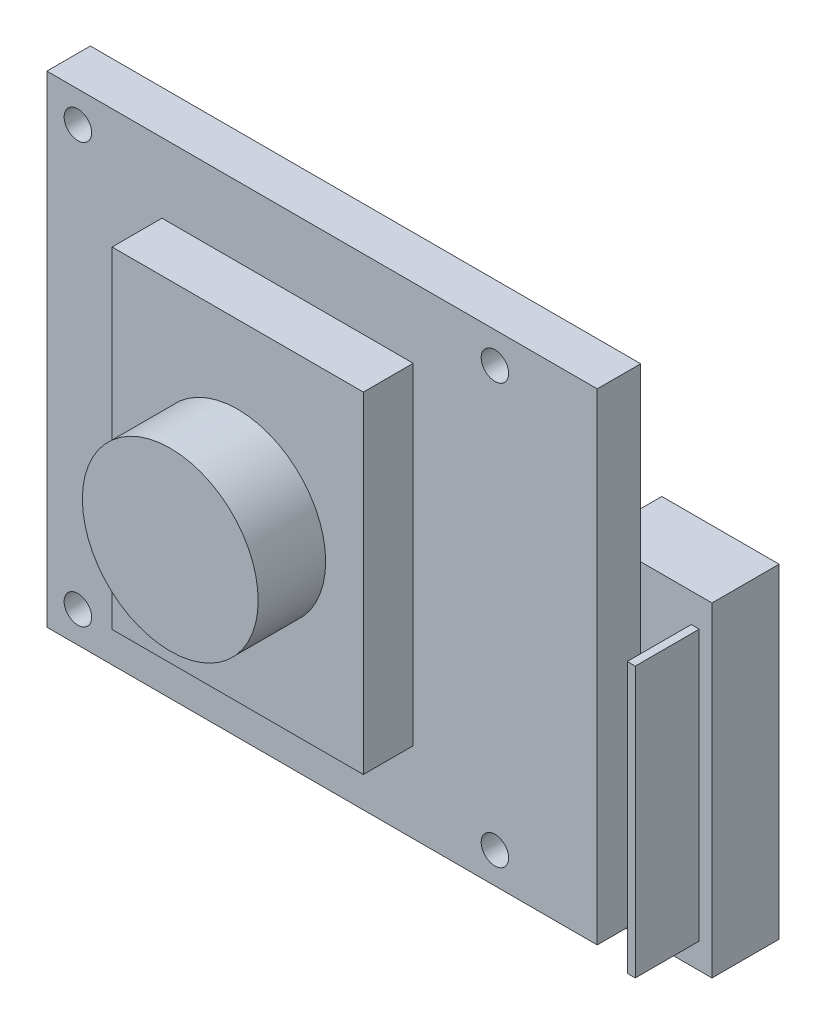
SolidWorks part; units mm, degrees
ref_plane "Front Plane" through (0, 0, 0) normal (0, 0, 1) x (1, 0, 0)
ref_plane "Top Plane" through (0, 0, 0) normal (0, 1, 0) x (1, 0, 0)
ref_plane "Right Plane" through (0, 0, 0) normal (1, 0, 0) x (0, 0, -1)
sketch "Sketch1" plane through (0, 0, 0) normal (0, 0, 1) x (1, 0, 0)
  line L1 (-43.7261, 0) -> (0, 0)
  line L2 (-43.7261, 0) -> (-43.7261, 38.2651)
  line L3 (-43.7261, 38.2651) -> (0, 38.2651)
  line L4 (0, 0) -> (0, 38.2651)
  dimension "D1" = 38.2651
  dimension "D2" = 43.7261
extrude "Boss-Extrude1" add sketch "Sketch1" along normal blind 3.4544
sketch "Sketch2" plane through (0, 0, 0) normal (0, 0, -1) x (-1, 0, 0)
  line L0 (0, 0) -> (0, 38.2651) construction
  line L1 (3.6576, -1.1684) -> (-5.6642, -1.1684)
  line L2 (3.6576, -1.1684) -> (3.6576, 24.638)
  line L3 (3.6576, 24.638) -> (-5.6642, 24.638)
  line L4 (-5.6642, -1.1684) -> (-5.6642, 24.638)
  line L5 (43.7261, 0) -> (0, 0) construction
  dimension "D1" = 9.3218
  dimension "D2" = 25.8064
  dimension "D3" = 5.6642
  dimension "D4" = 1.1684
extrude "Boss-Extrude2" add sketch "Sketch2" along normal blind 5.334
sketch "Sketch3" plane through (0, 0, 0) normal (0, 0, 1) x (1, 0, 0)
  line L0 (5.6642, 24.638) -> (5.6642, -1.1684) construction
  line L1 (4.0132, 0.8636) -> (4.6482, 0.8636)
  line L2 (4.0132, 0.8636) -> (4.0132, 22.3266)
  line L3 (4.0132, 22.3266) -> (4.6482, 22.3266)
  line L4 (4.6482, 0.8636) -> (4.6482, 22.3266)
  line L5 (5.6642, -1.1684) -> (-3.6576, -1.1684) construction
  dimension "D1" = 21.463
  dimension "D2" = 0.635
  dimension "D3" = 1.016
  dimension "D4" = 2.032
extrude "Boss-Extrude3" add sketch "Sketch3" along normal blind 5.08
sketch "Sketch4" plane through (0, 0, 0) normal (0, 0, -1) x (-1, 0, 0)
  line L2 (0, 38.2651) -> (43.7261, 38.2651) construction
  line L3 (43.7261, 38.2651) -> (43.7261, 0) construction
  line L4 (43.7261, 0) -> (3.6576, 0) construction
  line L5 (0, 24.638) -> (0, 38.2651) construction
  circle A0 centre (41.2623, 35.8013) radius 1.0922
  circle A1 centre (41.2623, 2.4638) radius 1.0922
  circle A2 centre (8.128, 2.4638) radius 1.0922
  circle A3 centre (8.128, 35.8013) radius 1.0922
  dimension "D1" = 2.1844
  dimension "D2" = 2.4638
  dimension "D4" = 2.1844
  dimension "D8" = 2.1844
  dimension "D9" = 2.1844
  dimension "D3" = 2.4638
  dimension "D5" = 2.4638
  dimension "D6" = 2.4638
  dimension "D7" = 2.4638
  dimension "D10" = 2.4638
  dimension "D11" = 8.128
extrude "Cut-Extrude1" cut sketch "Sketch4" against normal blind 5.08
sketch "Sketch5" plane through (0, 0, 3.4544) normal (0, 0, 1) x (1, 0, 0)
  line L0 (-43.7261, 0) -> (0, 0) construction
  line L1 (-34.5821, 6.4008) -> (-14.6177, 6.4008)
  line L2 (-34.5821, 6.4008) -> (-34.5821, 32.7152)
  line L3 (-34.5821, 32.7152) -> (-14.6177, 32.7152)
  line L4 (-14.6177, 6.4008) -> (-14.6177, 32.7152)
  line L5 (-43.7261, 38.2651) -> (-43.7261, 0) construction
  dimension "D1" = 26.3144
  dimension "D2" = 19.9644
  dimension "D3" = 6.4008
  dimension "D4" = 9.144
extrude "Boss-Extrude4" add sketch "Sketch5" along normal blind 3.9624
ref_plane "Plane1" through (0, 0, 12.7762) normal (0, 0, -1) x (-1, 0, 0)
sketch "Sketch6" plane through (0, 0, 12.7762) normal (0, 0, -1) x (-1, 0, 0)
  line L4 (34.5821, 6.4008) -> (34.5821, 32.7152)
  line L5 (14.6177, 6.4008) -> (34.5821, 6.4008)
  line L6 (14.6177, 32.7152) -> (14.6177, 6.4008)
  line L7 (34.5821, 32.7152) -> (14.6177, 32.7152)
  line L8 (34.5821, 6.4008) -> (34.5821, 32.7152) construction
  line L9 (14.6177, 6.4008) -> (34.5821, 6.4008) construction
  line L10 (14.6177, 32.7152) -> (14.6177, 6.4008) construction
  line L11 (34.5821, 32.7152) -> (14.6177, 32.7152) construction
  circle A0 centre (24.5999, 19.558) radius 6.985
  dimension "D1" = 13.97
  dimension "D3" = 9.9822
  dimension "D4" = 13.1572
  dimension "D2" = 0
extrude "Boss-Extrude5" add sketch "Sketch6" along normal blind 6.5024
sketch "Sketch7" plane through (0, 0, 0) normal (0, 0, -1) x (-1, 0, 0)
  line L0 (43.7261, 0) -> (3.6576, 0) construction
  line L1 (43.7261, 38.2651) -> (43.7261, 0) construction
  circle A0 centre (25.4381, 30.0482) radius 1.524
  circle A1 centre (25.4381, 8.128) radius 1.524
  dimension "D1" = 21.9202
  dimension "D2" = 3.048
  dimension "D3" = 3.048
  dimension "D4" = 8.128
  dimension "D5" = 18.288
extrude "Boss-Extrude6" add sketch "Sketch7" along normal blind 3.6195
